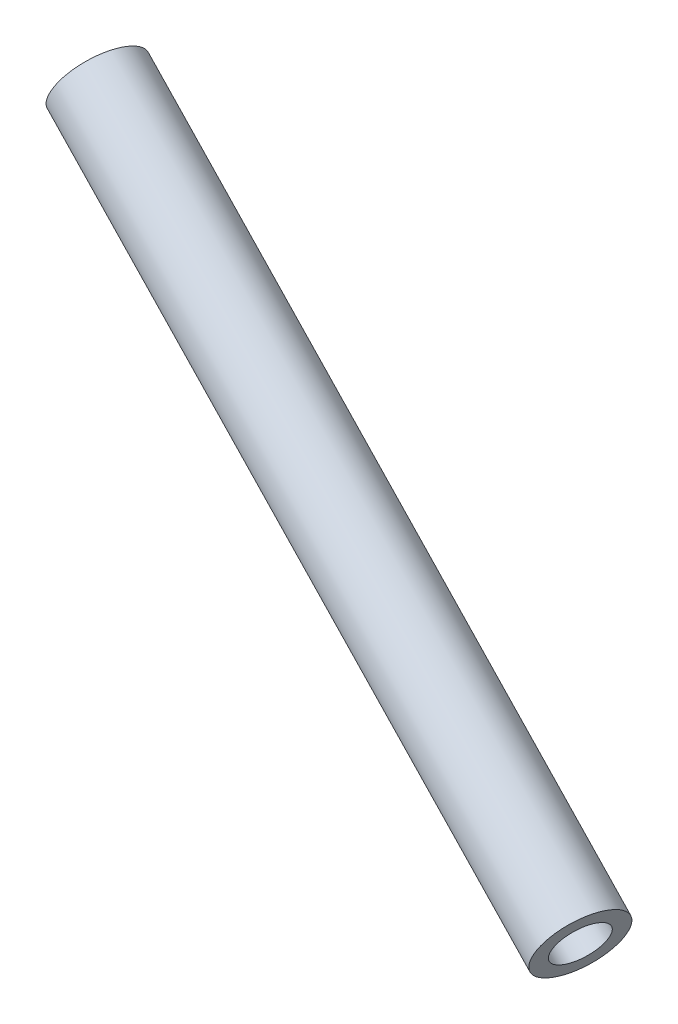
SolidWorks part; units mm, degrees
other "Compression Outer Sleeve"
other "Compression Outer Sleeve Left"
ref_plane "Front Plane" through (0, 0, 0) normal (0, 0, 1) x (1, 0, 0)
ref_plane "Top Plane" through (0, 0, 0) normal (0, 1, 0) x (1, 0, 0)
ref_plane "Right Plane" through (0, 0, 0) normal (1, 0, 0) x (0, 0, -1)
sketch3d "Sliding sleeve outside sketch datum points"
  point P0 (-34.1193, -76.9152, -2.0974)
  point P1 (-29.1842, -84.5818, -6.2045)
  point P2 (-34.1193, -81.6374, 6.7174)
ref_plane "Sliding sleeve outside sketch plane" through (-55.3357, -27.6774, -14.8272) normal (-0.8697, -0.435, -0.233) x (-0.2084, -0.1043, 0.9725)
sketch "Sliding sleeve outside sketch" plane through (-55.3357, -27.6774, -14.8272) normal (-0.8697, -0.435, -0.233) x (-0.2084, -0.1043, 0.9725)
  circle A0 centre (13.0902, -53.5275) radius 2.5
extrude "Sliding sleeve outside" add sketch "Sliding sleeve outside sketch" along normal blind 46.3649 separate body
sketch3d "Sliding sleeve bore sketch datum points"
  point P0 (-34.0323, -76.8717, -2.0741)
  point P1 (-29.0972, -84.5383, -6.1812)
  point P2 (-34.0323, -81.5939, 6.7407)
ref_plane "Sliding sleeve bore sketch plane" through (-55.2488, -27.6339, -14.8039) normal (-0.8697, -0.435, -0.233) x (-0.2084, -0.1043, 0.9725)
sketch "Sliding sleeve bore sketch" plane through (-55.2488, -27.6339, -14.8039) normal (-0.8697, -0.435, -0.233) x (-0.2084, -0.1043, 0.9725)
  circle A0 centre (13.0902, -53.5275) radius 1.55
extrude "Sliding sleeve bore" cut sketch "Sliding sleeve bore sketch" along normal blind 46.5649
sketch3d "Mirror1 profile datum points"
  point P0 (0, 0, 0)
  point P1 (10, 0, 0)
  point P2 (0, 0, 10)
ref_plane "Mirror1 profile plane" through (0, 0, 0) normal (0, -1, 0) x (-1, 0, 0)
mirror "Mirror1" about plane through (0, 0, 0) normal (0, -1, 0) of bodies 102
delete or keep bodies "Remove1" type delete bodies bodies 102
